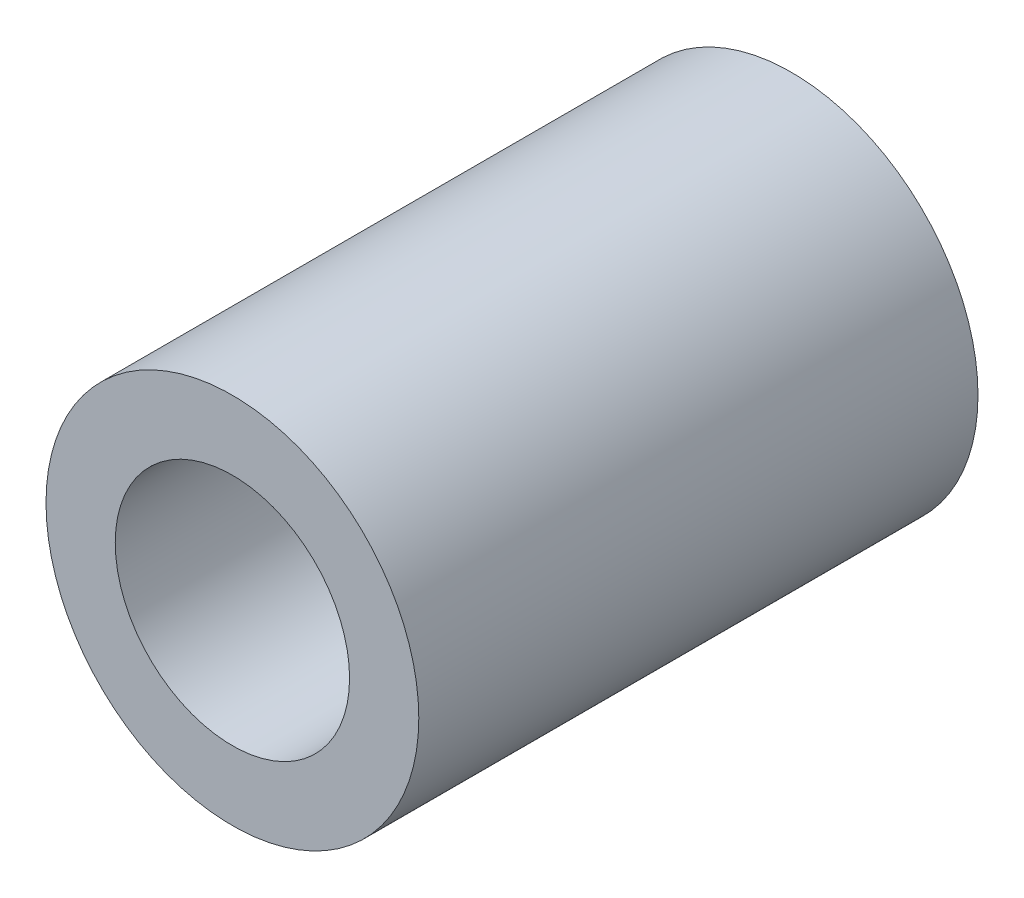
SolidWorks part; units mm, degrees
ref_plane "Front Plane" through (0, 0, 0) normal (0, 0, 1) x (1, 0, 0)
ref_plane "Top Plane" through (0, 0, 0) normal (0, 1, 0) x (1, 0, 0)
ref_plane "Right Plane" through (0, 0, 0) normal (1, 0, 0) x (0, 0, -1)
sketch "Sketch1" plane through (0, 0, 0) normal (0, 0, 1) x (1, 0, 0)
  circle A0 centre (0, 0) radius 4.4
  circle A1 centre (0, 0) radius 7
extrude "Boss-Extrude1" add sketch "Sketch1" along normal blind 21
